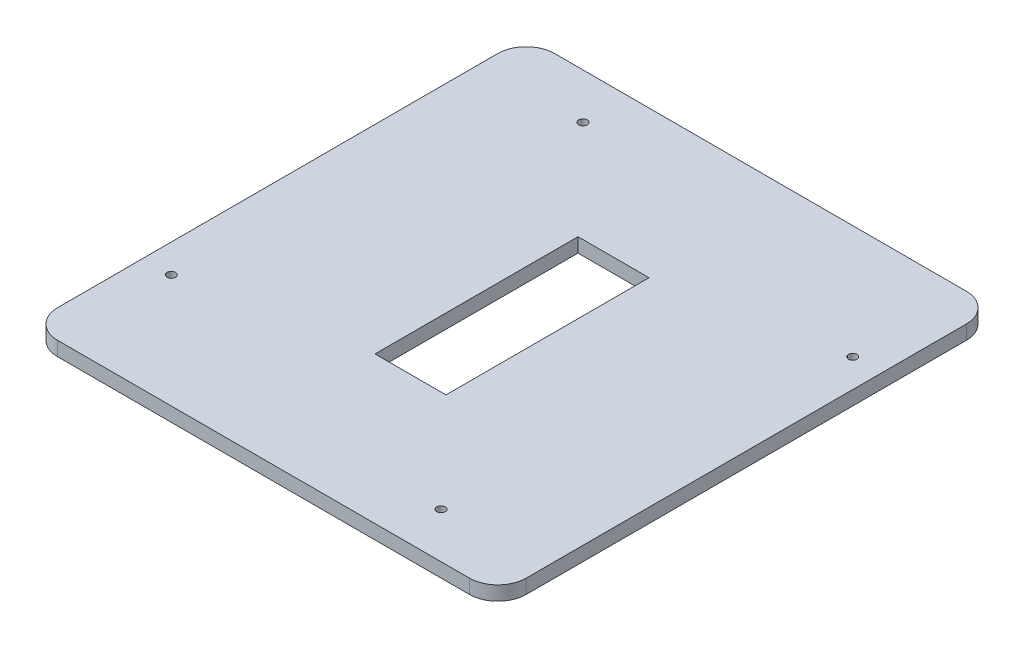
SolidWorks part; units mm, degrees
material "Acrílico (médio-alto impacto)"
ref_plane "Plano frontal" through (0, 0, 0) normal (0, 0, 1) x (1, 0, 0)
ref_plane "Plano superior" through (0, 0, 0) normal (0, 1, 0) x (1, 0, 0)
ref_plane "Plano direito" through (0, 0, 0) normal (1, 0, 0) x (0, 0, -1)
sketch "Esboço1" plane through (0, 0, 0) normal (0, 1, 0) x (1, 0, 0)
  line L1 (-25.4636, 142.2644) -> (119.5364, 142.2644)
  line L2 (-35.4636, 132.2644) -> (-35.4636, -22.7356)
  line L3 (-25.4636, -32.7356) -> (119.5364, -32.7356)
  line L4 (129.5364, 132.2644) -> (129.5364, -22.7356)
  arc A0 (119.5364, 142.2644) -> (129.5364, 132.2644) centre (119.5364, 132.2644) cw
  arc A1 (119.5364, -32.7356) -> (129.5364, -22.7356) centre (119.5364, -22.7356) ccw
  arc A2 (-35.4636, -22.7356) -> (-25.4636, -32.7356) centre (-25.4636, -22.7356) ccw
  arc A3 (-25.4636, 142.2644) -> (-35.4636, 132.2644) centre (-25.4636, 132.2644) ccw
  arc A4 (119.5364, 142.2644) -> (129.5364, 132.2644) centre (119.5364, 132.2644) cw
  dimension "D1" = 10
  dimension "D2" = 10
extrude "Ressalto-extrusão1" add sketch "Esboço1" along normal blind 5 contours L1 A3 L2 A2 L3 A1 L4 A0
sketch "Esboço2" plane through (0, 5, 0) normal (0, 1, 0) x (1, 0, 0)
  line L0 (-35.4636, 132.2644) -> (-35.4636, -22.7356) construction
  line L1 (-25.4636, -32.7356) -> (119.5364, -32.7356) construction
  line L2 (129.5364, 132.2644) -> (129.5364, -22.7356) construction
  line L3 (-25.4636, 142.2644) -> (119.5364, 142.2644) construction
  circle A0 centre (-25.4636, 7.2644) radius 1.5
  circle A1 centre (0.5364, 126.2644) radius 1.5
  circle A2 centre (119.5364, 102.2644) radius 1.5
  circle A3 centre (93.5364, -16.7356) radius 1.5
  dimension "D1" = 10
  dimension "D2" = 40
  dimension "D3" = 10
  dimension "D4" = 40
  dimension "D5" = 16
  dimension "D6" = 36
  dimension "D7" = 36
  dimension "D8" = 16
  dimension "D9" = 3
  dimension "D10" = 3
  dimension "D11" = 3
  dimension "D12" = 3
extrude "Corte-extrusão1" cut sketch "Esboço2" against normal blind 5
sketch "Esboço3" plane through (0, 5, 0) normal (0, 1, 0) x (1, 0, 0)
  line L0 (-25.4636, 142.2644) -> (119.5364, 142.2644) construction
  line L1 (34.5364, 90.5144) -> (59.5364, 90.5144)
  line L2 (34.5364, 90.5144) -> (34.5364, 19.0144)
  line L3 (34.5364, 19.0144) -> (59.5364, 19.0144)
  line L4 (59.5364, 90.5144) -> (59.5364, 19.0144)
  line L8 (-25.4636, -32.7356) -> (119.5364, -32.7356) construction
  line L9 (129.5364, 132.2644) -> (129.5364, -22.7356) construction
  line L11 (-35.4636, 132.2644) -> (-35.4636, -22.7356) construction
  dimension "D1" = 25
  dimension "D2" = 51.75
  dimension "D3" = 51.75
  dimension "D4" = 70
  dimension "D5" = 70
extrude "Corte-extrusão2" cut sketch "Esboço3" against normal blind 5
